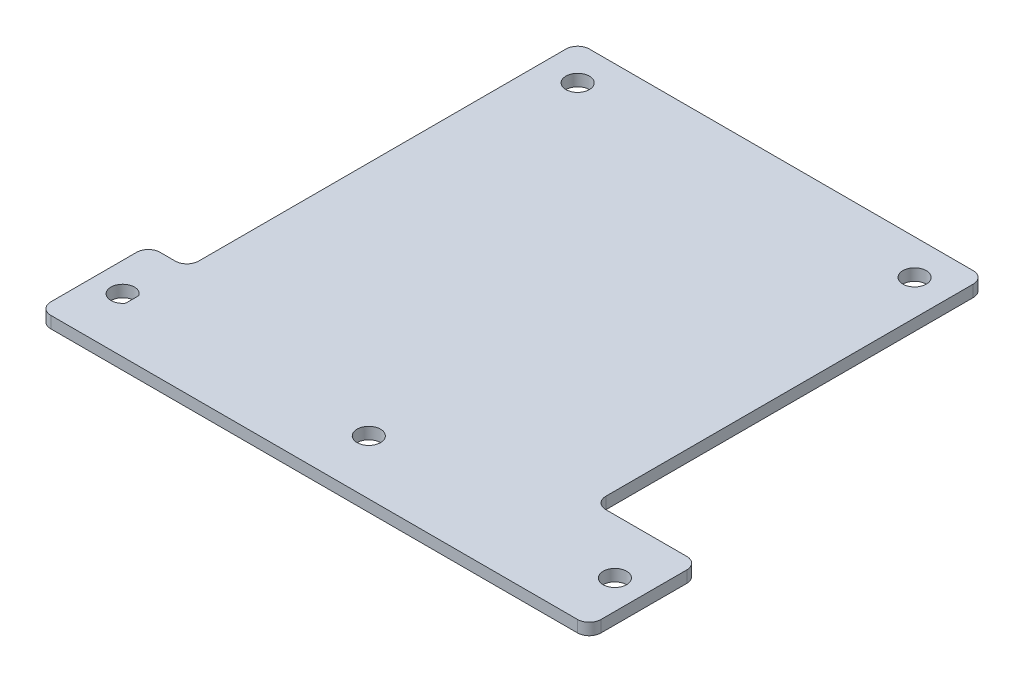
SolidWorks part; units mm, degrees
ref_plane "Front Plane" through (0, 0, 0) normal (0, 0, 1) x (1, 0, 0)
ref_plane "Top Plane" through (0, 0, 0) normal (0, 1, 0) x (1, 0, 0)
ref_plane "Right Plane" through (0, 0, 0) normal (1, 0, 0) x (0, 0, -1)
sketch "Sketch1" plane through (0, 0, 0) normal (0, 1, 0) x (1, 0, 0)
  line L0 (4.75, -35) -> (-28.75, -35)
  line L1 (28.75, 35) -> (-28.75, 35)
  line L2 (28.75, 35) -> (28.75, -35)
  line L3 (28.75, -35) -> (-28.75, -35)
  line L4 (-28.75, 35) -> (-28.75, -35)
  line L5 (28.75, 35) -> (-28.75, -35) construction
  line L6 (28.75, -35) -> (-28.75, 35) construction
  line L7 (34.75, 41) -> (-34.75, 41)
  line L8 (34.75, 41) -> (34.75, -41)
  line L9 (34.75, -41) -> (-34.75, -41)
  line L10 (-34.75, 41) -> (-34.75, -41)
  line L11 (34.75, 41) -> (-34.75, -41) construction
  line L12 (34.75, -41) -> (-34.75, 41) construction
  line L13 (28.75, -35) -> (4.75, -35)
  line L14 (-28.75, -35) -> (5.6028, -35)
  circle A0 centre (-28.75, 35) radius 2
  circle A1 centre (28.75, 35) radius 2
  circle A2 centre (5.6028, -35) radius 2
  point P0 (0, 0)
  point P6 (0, 0)
  dimension "D6" = 4
  dimension "D7" = 4
  dimension "D10" = 4
  dimension "D1" = 57.5
  dimension "D2" = 70
  dimension "D3" = 6
  dimension "D4" = 6
  dimension "D5" = 6
  dimension "D8" = 33.5
  dimension "D9" = 24
extrude "Boss-Extrude1" add sketch "Sketch1" along normal blind 2 contours L7 L10 L9 L8 A2 L14 L4 A0 L1 A1 L2 L3 | A2 L3 L2 A1 L1 A0 L4 L14
sketch "Sketch2" plane through (0, 2, 0) normal (0, 1, 0) x (1, 0, 0)
  line L2 (5.6028, -35) -> (-36.3972, -35)
  line L3 (5.6028, -35) -> (47.6028, -35)
  line L5 (47.6028, -29.0354) -> (-36.3972, -29.0354)
  line L6 (47.6028, -29.0354) -> (47.6028, -40.9646)
  line L7 (47.6028, -40.9646) -> (-36.3972, -40.9646)
  line L8 (-36.3972, -29.0354) -> (-36.3972, -40.9646)
  line L9 (47.6028, -29.0354) -> (-36.3972, -40.9646) construction
  line L10 (47.6028, -40.9646) -> (-36.3972, -29.0354) construction
  line L11 (52.549, -25.6803) -> (-41.3434, -25.6803)
  line L12 (52.549, -25.6803) -> (52.549, -44.3197)
  line L13 (52.549, -44.3197) -> (-41.3434, -44.3197)
  line L14 (-41.3434, -25.6803) -> (-41.3434, -44.3197)
  line L15 (52.549, -25.6803) -> (-41.3434, -44.3197) construction
  line L16 (52.549, -44.3197) -> (-41.3434, -25.6803) construction
  circle A0 centre (-36.3972, -35) radius 2
  circle A1 centre (47.6028, -35) radius 2
  circle M3 centre (5.6028, -35) radius 2
  line M7 (-34.75, 41) -> (-34.75, -41)
  line M8 (-34.75, -41) -> (34.75, -41)
  line M9 (34.75, -41) -> (34.75, 41)
  dimension "D3" = 4
  dimension "D4" = 4
  dimension "D1" = 42
  dimension "D2" = 42
extrude "Boss-Extrude3" add sketch "Sketch2" against normal blind 2 contours A1 L6 L7 L8 A0 L5 L11 L14 L13 L12 M9 M8 M7 | A0 L7 L3 L2 M7 M9 M3 | A0 L2 L3 L5 M3 M9 M7 | A1 L3 L7 L6 M9 | A1 L6 L5 L3 M9 | A0 L8 L7 M7 | A0 L5 L8 M7
fillet "Fillet1" radius 2 8 edges at (34.75, 1, 25.6803) (-34.75, 1, 25.6803) (-41.3434, 1, 44.3197) (-41.3434, 1, 25.6803) (-34.75, 1, -41) (34.75, 1, -41) (52.549, 1, 25.6803) (52.549, 1, 44.3197)
